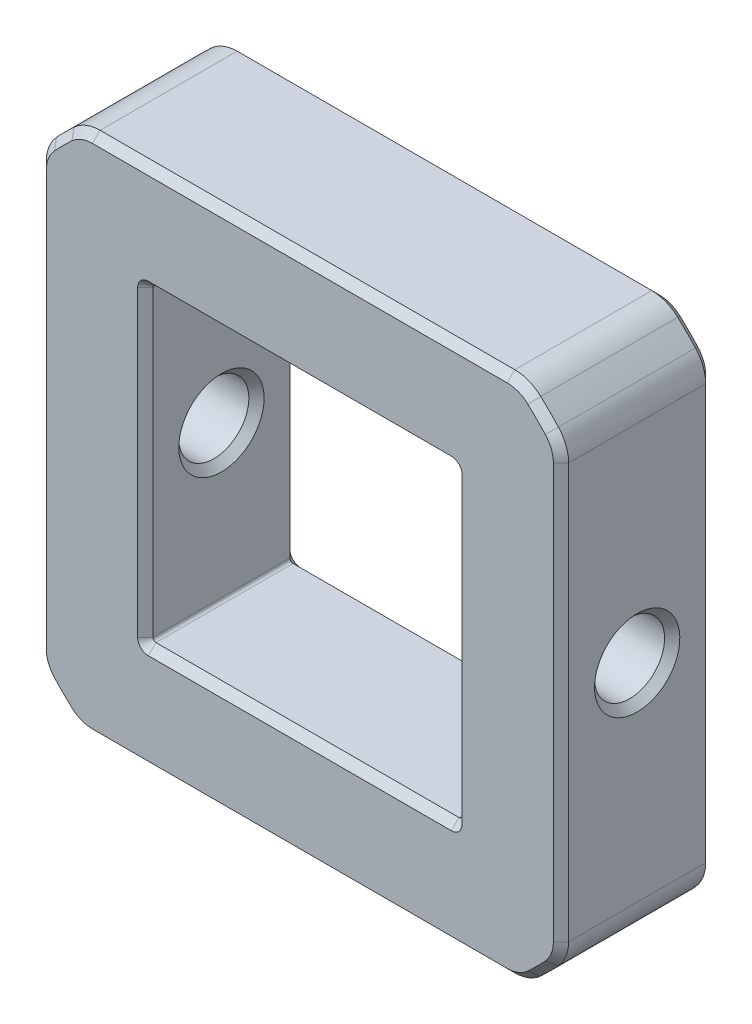
SolidWorks part; units mm, degrees
ref_plane "Front" through (0, 0, 0) normal (0, 0, 1) x (1, 0, 0)
ref_plane "Top" through (0, 0, 0) normal (0, 1, 0) x (1, 0, 0)
ref_plane "Right" through (0, 0, 0) normal (1, 0, 0) x (0, 0, -1)
sketch "Skizze1" plane through (0, 0, 0) normal (0, 0, 1) x (1, 0, 0)
  line L0 (14.5646, 17.15) -> (-14.5646, 17.15)
  line L1 (-10.15, -10.15) -> (10.15, -10.15)
  line L2 (-10.15, -10.15) -> (-10.15, 10.15)
  line L3 (-10.15, 10.15) -> (10.15, 10.15)
  line L4 (10.15, -10.15) -> (10.15, 10.15)
  line L5 (-10.15, -10.15) -> (10.15, 10.15) construction
  line L6 (-10.15, 10.15) -> (10.15, -10.15) construction
  line L7 (17.15, 14.5646) -> (17.15, -14.5646)
  line L8 (-14.5646, -17.15) -> (14.5646, -17.15)
  line L9 (-17.15, -14.5646) -> (-17.15, 14.5646)
  arc A0 (-17.15, -14.5646) -> (-14.5646, -17.15) centre (0, 0) ccw
  arc A1 (-14.5646, 17.15) -> (-17.15, 14.5646) centre (0, 0) ccw
  arc A2 (17.15, 14.5646) -> (14.5646, 17.15) centre (0, 0) ccw
  arc A3 (14.5646, -17.15) -> (17.15, -14.5646) centre (0, 0) ccw
  dimension "D1" = 45
  dimension "D2" = 20.3
  dimension "D3" = 7
extrude "Aufsatz-Linear austragen1" add sketch "Skizze1" along normal blind 10
fillet "Verrundung1" radius 0.2 4 edges at (10.15, -10.15, 5) (-10.15, -10.15, 5) (-10.15, 10.15, 5) (10.15, 10.15, 5)
fillet "Verrundung2" radius 2.5 8 edges at (14.5646, 17.15, 5) (17.15, 14.5646, 5) (17.15, -14.5646, 5) (14.5646, -17.15, 5) (-14.5646, -17.15, 5) (-17.15, -14.5646, 5) (-17.15, 14.5646, 5) (-14.5646, 17.15, 5)
sketch "Skizze2" plane through (17.15, 0, 0) normal (1, 0, 0) x (0, 0, -1)
  line L0 (0, 0) -> (-10, 0) construction
  line L1 (-10, -13.6153) -> (-10, 13.6153) construction
  circle A0 centre (-5, 0) radius 2.3
  dimension "D1" = 4.6
extrude "Schnitt-Linear austragen1" cut sketch "Skizze2" against normal through all
chamfer "Fase2" distance 0.5 angle 45 52 edges at (17.15, 2.3, 5) (10.15, 0, 7.3) (-17.15, 2.3, 5) (-10.15, 0, 2.7) (-10.0914, 10.0914, 10) (-10.15, 0, 10) (-10.0914, -10.0914, 10) (0, -10.15, 10) (10.0914, -10.0914, 10) (10.15, 0, 10) (10.0914, 10.0914, 10) (0, 10.15, 10) (16.9768, 14.5296, 10) (17.15, 0, 10) (16.9768, -14.5296, 10) (15.9099, -15.9099, 10) (14.5296, -16.9768, 10) (0, -17.15, 10) (-14.5296, -16.9768, 10) (-15.9099, -15.9099, 10) (-16.9768, -14.5296, 10) (-17.15, 0, 10) (-16.9768, 14.5296, 10) (-15.9099, 15.9099, 10) (-14.5296, 16.9768, 10) (0, 17.15, 10) (14.5296, 16.9768, 10) (15.9099, 15.9099, 10) (-10.0914, -10.0914, 0) (-10.15, 0, 0) (-10.0914, 10.0914, 0) (0, 10.15, 0) (10.0914, 10.0914, 0) (10.15, 0, 0) (10.0914, -10.0914, 0) (0, -10.15, 0) (-14.5296, 16.9768, 0) (-15.9099, 15.9099, 0) (-16.9768, 14.5296, 0) (-17.15, 0, 0) (-16.9768, -14.5296, 0) (-15.9099, -15.9099, 0) (-14.5296, -16.9768, 0) (0, -17.15, 0) (14.5296, -16.9768, 0) (15.9099, -15.9099, 0) (16.9768, -14.5296, 0) (17.15, 0, 0) (16.9768, 14.5296, 0) (15.9099, 15.9099, 0) (14.5296, 16.9768, 0) (0, 17.15, 0)
